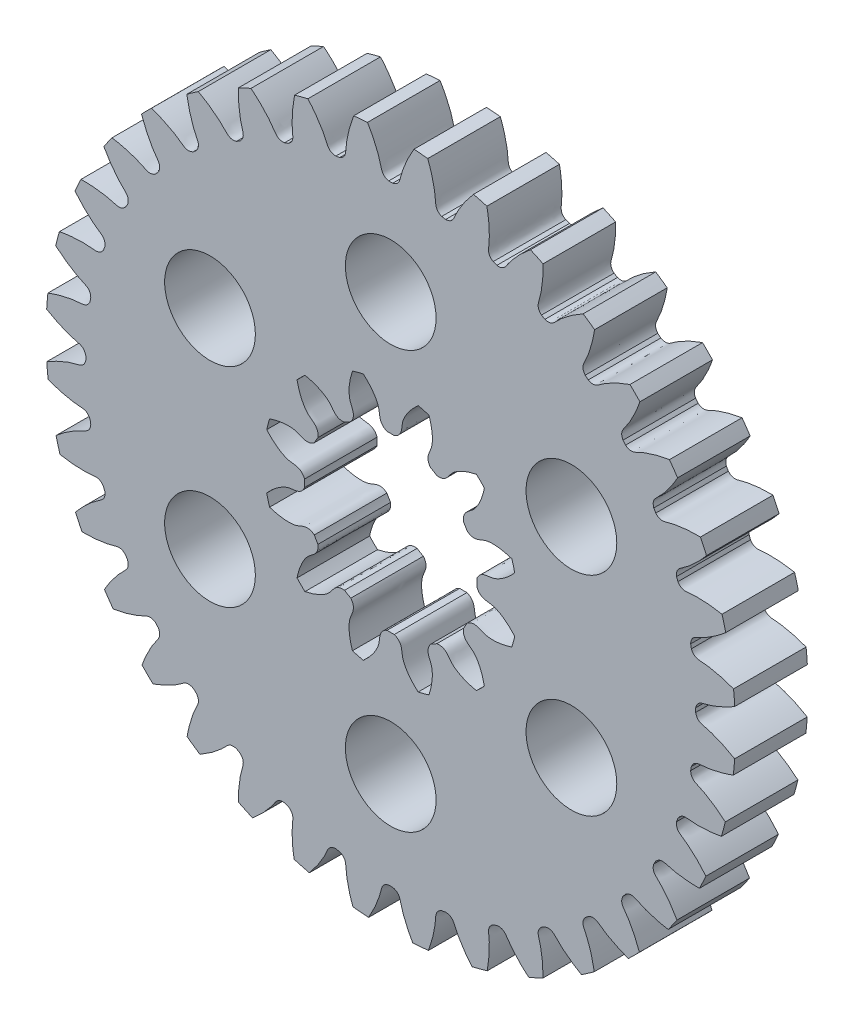
SolidWorks part; units mm, degrees
ref_plane "前视基准面" through (0, 0, 0) normal (0, 0, 1) x (1, 0, 0)
ref_plane "上视基准面" through (0, 0, 0) normal (0, 1, 0) x (1, 0, 0)
ref_plane "右视基准面" through (0, 0, 0) normal (1, 0, 0) x (0, 0, -1)
sketch "草图1" plane through (0, 0, 0) normal (0, 0, 1) x (1, 0, 0)
  arc A0 (-261.7659, -219.3873) -> (-261.9823, -219.4255) centre (-258.9656, -235.9016) ccw
  arc A1 (-258.8462, -219.1511) -> (-259.0659, -219.1511) centre (-258.956, -235.9007) ccw
  arc A2 (-256.9161, -217.0106) -> (-257.675, -216.944) centre (-258.956, -235.9007) ccw
  arc A3 (-255.9297, -219.4255) -> (-256.1461, -219.3873) centre (-258.9464, -235.9016) ccw
  arc A4 (-253.1052, -220.2021) -> (-253.3117, -220.127) centre (-258.9372, -235.9041) ccw
  arc A5 (-250.4585, -221.4574) -> (-250.6488, -221.3476) centre (-258.9285, -235.9081) ccw
  arc A6 (-248.07, -223.1533) -> (-248.2383, -223.012) centre (-258.9206, -235.9136) ccw
  arc A7 (-246.0122, -225.2381) -> (-246.1534, -225.0698) centre (-258.9138, -235.9204) ccw
  arc A8 (-244.3477, -227.6486) -> (-244.4576, -227.4583) centre (-258.9083, -235.9283) ccw
  arc A9 (-243.1271, -230.3116) -> (-243.2023, -230.1051) centre (-258.9042, -235.937) ccw
  arc A10 (-242.3875, -233.146) -> (-242.4256, -232.9296) centre (-258.9017, -235.9463) ccw
  arc A11 (-242.1512, -236.0658) -> (-242.1512, -235.846) centre (-258.9009, -235.9559) ccw
  arc A12 (-242.4256, -238.9822) -> (-242.3875, -238.7658) centre (-258.9017, -235.9655) ccw
  arc A13 (-243.2023, -241.8067) -> (-243.1271, -241.6002) centre (-258.9042, -235.9747) ccw
  arc A14 (-244.4576, -244.4534) -> (-244.3477, -244.2631) centre (-258.9083, -235.9835) ccw
  arc A15 (-246.1534, -246.842) -> (-246.0122, -246.6736) centre (-258.9138, -235.9913) ccw
  arc A16 (-248.2383, -248.8997) -> (-248.07, -248.7585) centre (-258.9206, -235.9981) ccw
  arc A17 (-250.6488, -250.5642) -> (-250.4585, -250.4543) centre (-258.9285, -236.0036) ccw
  arc A18 (-253.3117, -251.7848) -> (-253.1052, -251.7096) centre (-258.9372, -236.0077) ccw
  arc A19 (-256.1461, -252.5245) -> (-255.9297, -252.4863) centre (-258.9464, -236.0102) ccw
  arc A20 (-259.0659, -252.7607) -> (-258.8462, -252.7607) centre (-258.956, -236.011) ccw
  arc A21 (-261.9823, -252.4863) -> (-261.7659, -252.5245) centre (-258.9656, -236.0102) ccw
  arc A22 (-264.8068, -251.7096) -> (-264.6004, -251.7848) centre (-258.9749, -236.0077) ccw
  arc A23 (-267.4536, -250.4543) -> (-267.2633, -250.5642) centre (-258.9836, -236.0036) ccw
  arc A24 (-269.8421, -248.7585) -> (-269.6738, -248.8997) centre (-258.9915, -235.9981) ccw
  arc A25 (-271.8999, -246.6736) -> (-271.7586, -246.842) centre (-258.9983, -235.9913) ccw
  arc A26 (-273.5643, -244.2631) -> (-273.4545, -244.4534) centre (-259.0038, -235.9835) ccw
  arc A27 (-274.7849, -241.6002) -> (-274.7098, -241.8067) centre (-259.0079, -235.9747) ccw
  arc A28 (-275.5246, -238.7658) -> (-275.4864, -238.9822) centre (-259.0103, -235.9655) ccw
  arc A29 (-275.7608, -235.846) -> (-275.7608, -236.0658) centre (-259.0112, -235.9559) ccw
  arc A30 (-275.4864, -232.9296) -> (-275.5246, -233.146) centre (-259.0103, -235.9463) ccw
  arc A31 (-274.7098, -230.1051) -> (-274.7849, -230.3116) centre (-259.0079, -235.937) ccw
  arc A32 (-273.4545, -227.4583) -> (-273.5643, -227.6486) centre (-259.0038, -235.9283) ccw
  arc A33 (-271.7586, -225.0698) -> (-271.8999, -225.2381) centre (-258.9983, -235.9204) ccw
  arc A34 (-269.6738, -223.012) -> (-269.8421, -223.1533) centre (-258.9915, -235.9136) ccw
  arc A35 (-267.2633, -221.3476) -> (-267.4536, -221.4574) centre (-258.9836, -235.9081) ccw
  arc A36 (-264.6004, -220.127) -> (-264.8068, -220.2021) centre (-258.9749, -235.9041) ccw
  arc A37 (-253.6569, -217.6547) -> (-254.3942, -217.4565) centre (-258.956, -235.9007) ccw
  arc A38 (-250.5593, -218.8568) -> (-251.2538, -218.5319) centre (-258.956, -235.9007) ccw
  arc A39 (-247.7186, -220.5802) -> (-248.3498, -220.1366) centre (-258.956, -235.9007) ccw
  arc A40 (-245.2217, -222.7719) -> (-245.7703, -222.2209) centre (-258.956, -235.9007) ccw
  arc A41 (-243.145, -225.3645) -> (-243.5936, -224.7206) centre (-258.956, -235.9007) ccw
  arc A42 (-241.5521, -228.2783) -> (-241.8852, -227.5588) centre (-258.956, -235.9007) ccw
  arc A43 (-240.491, -231.4237) -> (-240.6963, -230.6488) centre (-258.956, -235.9007) ccw
  arc A44 (-239.9937, -234.7044) -> (-240.062, -233.8965) centre (-258.956, -235.9007) ccw
  arc A45 (-240.0746, -238.02) -> (-240.0007, -237.2032) centre (-258.956, -235.9007) ccw
  arc A46 (-240.7303, -241.2693) -> (-240.5134, -240.4689) centre (-258.956, -235.9007) ccw
  arc A47 (-241.9398, -244.3535) -> (-241.5837, -243.595) centre (-258.956, -235.9007) ccw
  arc A48 (-243.6656, -247.1792) -> (-243.1788, -246.4875) centre (-258.956, -235.9007) ccw
  arc A49 (-245.8545, -249.6611) -> (-245.2501, -249.0593) centre (-258.956, -235.9007) ccw
  arc A50 (-248.4392, -251.7247) -> (-247.7349, -251.2333) centre (-258.956, -235.9007) ccw
  arc A51 (-251.3412, -253.308) -> (-250.5583, -252.9441) centre (-258.956, -235.9007) ccw
  arc A52 (-254.4722, -254.3641) -> (-253.6351, -254.1405) centre (-258.956, -235.9007) ccw
  arc A53 (-257.7377, -254.8616) -> (-256.873, -254.7862) centre (-258.956, -235.9007) ccw
  arc A54 (-261.0391, -254.7862) -> (-260.1743, -254.8616) centre (-258.956, -235.9007) ccw
  arc A55 (-264.2769, -254.1405) -> (-263.4398, -254.3641) centre (-258.956, -235.9007) ccw
  arc A56 (-267.3538, -252.9441) -> (-266.5709, -253.308) centre (-258.956, -235.9007) ccw
  arc A57 (-270.1771, -251.2333) -> (-269.4728, -251.7247) centre (-258.956, -235.9007) ccw
  arc A58 (-272.6619, -249.0593) -> (-272.0576, -249.6611) centre (-258.956, -235.9007) ccw
  arc A59 (-274.7332, -246.4875) -> (-274.2464, -247.1792) centre (-258.956, -235.9007) ccw
  arc A60 (-276.3283, -243.595) -> (-275.9722, -244.3535) centre (-258.956, -235.9007) ccw
  arc A61 (-277.3987, -240.4689) -> (-277.1818, -241.2693) centre (-258.956, -235.9007) ccw
  arc A62 (-277.9113, -237.2032) -> (-277.8375, -238.02) centre (-258.956, -235.9007) ccw
  arc A63 (-277.85, -233.8965) -> (-277.9183, -234.7044) centre (-258.956, -235.9007) ccw
  arc A64 (-277.2157, -230.6488) -> (-277.421, -231.4237) centre (-258.956, -235.9007) ccw
  arc A65 (-276.0268, -227.5588) -> (-276.36, -228.2783) centre (-258.956, -235.9007) ccw
  arc A66 (-274.3184, -224.7206) -> (-274.767, -225.3645) centre (-258.956, -235.9007) ccw
  arc A67 (-272.1417, -222.2209) -> (-272.6904, -222.7719) centre (-258.956, -235.9007) ccw
  arc A68 (-269.5623, -220.1366) -> (-270.1935, -220.5802) centre (-258.956, -235.9007) ccw
  arc A69 (-266.6582, -218.5319) -> (-267.3527, -218.8568) centre (-258.956, -235.9007) ccw
  arc A70 (-263.5178, -217.4565) -> (-264.2552, -217.6547) centre (-258.956, -235.9007) ccw
  arc A71 (-260.237, -216.944) -> (-260.996, -217.0106) centre (-258.956, -235.9007) ccw
  arc A72 (-260.4688, -229.0661) -> (-261.0633, -229.2254) centre (-258.956, -235.9007) ccw
  arc A73 (-258.7552, -231.155) -> (-259.1569, -231.155) centre (-258.956, -235.9007) ccw
  arc A74 (-256.8488, -229.2254) -> (-257.4433, -229.0661) centre (-258.956, -235.9007) ccw
  arc A75 (-256.4092, -231.8912) -> (-256.7571, -231.6904) centre (-258.956, -235.9007) ccw
  arc A76 (-253.7935, -231.1734) -> (-254.2287, -230.7382) centre (-258.956, -235.9007) ccw
  arc A77 (-254.7457, -233.7018) -> (-254.9465, -233.3539) centre (-258.956, -235.9007) ccw
  arc A78 (-252.1214, -234.388) -> (-252.2807, -233.7935) centre (-258.956, -235.9007) ccw
  arc A79 (-254.2103, -236.1016) -> (-254.2103, -235.6999) centre (-258.956, -235.9007) ccw
  arc A80 (-252.2807, -238.008) -> (-252.1214, -237.4135) centre (-258.956, -235.9007) ccw
  arc A81 (-254.9465, -238.4475) -> (-254.7457, -238.0997) centre (-258.956, -235.9007) ccw
  arc A82 (-254.2287, -241.0633) -> (-253.7935, -240.6281) centre (-258.956, -235.9007) ccw
  arc A83 (-256.7571, -240.1111) -> (-256.4092, -239.9103) centre (-258.956, -235.9007) ccw
  arc A84 (-257.4433, -242.7353) -> (-256.8488, -242.576) centre (-258.956, -235.9007) ccw
  arc A85 (-259.1569, -240.6465) -> (-258.7552, -240.6465) centre (-258.956, -235.9007) ccw
  arc A86 (-261.0633, -242.576) -> (-260.4688, -242.7353) centre (-258.956, -235.9007) ccw
  arc A87 (-261.5028, -239.9103) -> (-261.155, -240.1111) centre (-258.956, -235.9007) ccw
  arc A88 (-264.1186, -240.6281) -> (-263.6834, -241.0633) centre (-258.956, -235.9007) ccw
  arc A89 (-263.1664, -238.0997) -> (-262.9655, -238.4475) centre (-258.956, -235.9007) ccw
  arc A90 (-265.7906, -237.4135) -> (-265.6313, -238.008) centre (-258.956, -235.9007) ccw
  arc A91 (-263.7018, -235.6999) -> (-263.7018, -236.1016) centre (-258.956, -235.9007) ccw
  arc A92 (-265.6313, -233.7935) -> (-265.7906, -234.388) centre (-258.956, -235.9007) ccw
  arc A93 (-262.9655, -233.3539) -> (-263.1664, -233.7018) centre (-258.956, -235.9007) ccw
  arc A94 (-263.6834, -230.7382) -> (-264.1186, -231.1734) centre (-258.956, -235.9007) ccw
  arc A95 (-261.155, -231.6904) -> (-261.5028, -231.8912) centre (-258.956, -235.9007) ccw
  circle A96 centre (-258.956, -224.4007) radius 2.5
  circle A97 centre (-268.9153, -230.1507) radius 2.5
  circle A98 centre (-268.9153, -241.6507) radius 2.5
  circle A99 centre (-258.956, -247.4007) radius 2.5
  circle A100 centre (-248.9967, -241.6507) radius 2.5
  circle A101 centre (-248.9967, -230.1507) radius 2.5
  spline S0 degree 3 poles (-261.7659, -219.3873) (-261.4254, -219.2453) (-261.4414, -218.9757) (-261.4164, -218.6828) (-261.4078, -218.5991) (-261.3923, -218.4743) (-261.3655, -218.3022) (-261.3213, -218.0772) (-261.2618, -217.8279) (-261.1851, -217.5551) (-261.0957, -217.2795) (-261.0288, -217.0962) (-260.996, -217.0106) knots 0 0 0 0 0.120371 0.133303 0.147364 0.162556 0.19633 0.234626 0.277443 0.324782 0.376641 0.422597 0.422597 0.422597 0.422597
  spline S1 degree 3 poles (-259.0659, -219.1511) (-259.426, -219.0703) (-259.457, -218.8021) (-259.5325, -218.518) (-259.5555, -218.437) (-259.5925, -218.3168) (-259.6487, -218.152) (-259.7313, -217.9381) (-259.8332, -217.7029) (-259.9561, -217.4475) (-260.092, -217.1917) (-260.1898, -217.0227) (-260.237, -216.944) knots 0 0 0 0 0.120371 0.133303 0.147364 0.162556 0.19633 0.234626 0.277443 0.324782 0.376641 0.422634 0.422634 0.422634 0.422634
  spline S2 degree 3 poles (-258.8462, -219.1511) (-258.4861, -219.0703) (-258.455, -218.8021) (-258.3796, -218.518) (-258.3565, -218.437) (-258.3196, -218.3168) (-258.2634, -218.152) (-258.1807, -217.9381) (-258.0789, -217.7029) (-257.956, -217.4475) (-257.82, -217.1917) (-257.7223, -217.0227) (-257.675, -216.944) knots 0 0 0 0 0.120371 0.133303 0.147364 0.162556 0.19633 0.234626 0.277443 0.324782 0.376641 0.422634 0.422634 0.422634 0.422634
  spline S3 degree 3 poles (-256.1461, -219.3873) (-256.4867, -219.2453) (-256.4707, -218.9757) (-256.4956, -218.6828) (-256.5043, -218.5991) (-256.5198, -218.4743) (-256.5466, -218.3022) (-256.5908, -218.0772) (-256.6503, -217.8279) (-256.7269, -217.5551) (-256.8164, -217.2795) (-256.8833, -217.0962) (-256.9161, -217.0106) knots 0 0 0 0 0.120371 0.133303 0.147364 0.162556 0.19633 0.234626 0.277443 0.324782 0.376641 0.422597 0.422597 0.422597 0.422597
  spline S4 degree 3 poles (-255.9297, -219.4255) (-255.5611, -219.4085) (-255.4839, -219.1497) (-255.3603, -218.883) (-255.3235, -218.8073) (-255.2663, -218.6953) (-255.1823, -218.5428) (-255.0638, -218.3465) (-254.9226, -218.1325) (-254.7572, -217.9024) (-254.5793, -217.6744) (-254.454, -217.5254) (-254.3942, -217.4565) knots 0 0 0 0 0.120371 0.133303 0.147364 0.162556 0.19633 0.234626 0.277443 0.324782 0.376641 0.422355 0.422355 0.422355 0.422355
  spline S5 degree 3 poles (-253.3117, -220.127) (-253.6224, -219.9279) (-253.5599, -219.6653) (-253.5336, -219.3725) (-253.5276, -219.2885) (-253.5212, -219.1629) (-253.5176, -218.9888) (-253.5221, -218.7596) (-253.5374, -218.5037) (-253.5655, -218.2217) (-253.6057, -217.9355) (-253.6396, -217.744) (-253.6569, -217.6547) knots 0 0 0 0 0.120371 0.133303 0.147364 0.162556 0.19633 0.234626 0.277443 0.324782 0.376641 0.422247 0.422247 0.422247 0.422247
  spline S6 degree 3 poles (-253.1052, -220.2021) (-252.7392, -220.2494) (-252.6183, -220.008) (-252.4502, -219.7668) (-252.4009, -219.6986) (-252.3251, -219.5983) (-252.2159, -219.4626) (-252.0651, -219.2899) (-251.8889, -219.1037) (-251.6861, -218.9058) (-251.4721, -218.713) (-251.3237, -218.5887) (-251.2538, -218.5319) knots 0 0 0 0 0.120371 0.133303 0.147364 0.162556 0.19633 0.234626 0.277443 0.324782 0.376641 0.421771 0.421771 0.421771 0.421771
  spline S7 degree 3 poles (-250.6488, -221.3476) (-250.9202, -221.0976) (-250.813, -220.8498) (-250.7363, -220.566) (-250.7158, -220.4844) (-250.6877, -220.3618) (-250.654, -220.1909) (-250.6186, -219.9644) (-250.5892, -219.7098) (-250.5679, -219.4272) (-250.5578, -219.1397) (-250.5579, -218.9465) (-250.5593, -218.8568) knots 0 0 0 0 0.120371 0.133303 0.147364 0.162556 0.19633 0.234626 0.277443 0.324782 0.376641 0.421594 0.421594 0.421594 0.421594
  spline S8 degree 3 poles (-250.4585, -221.4574) (-250.1063, -221.5675) (-249.9453, -221.3508) (-249.7379, -221.1424) (-249.6774, -221.0839) (-249.5853, -220.9982) (-249.4542, -220.8836) (-249.2757, -220.7397) (-249.0699, -220.5869) (-248.8358, -220.4272) (-248.5931, -220.2754) (-248.4269, -220.1796) (-248.3498, -220.1366) knots 0 0 0 0 0.120371 0.133303 0.147364 0.162556 0.19633 0.234626 0.277443 0.324782 0.376641 0.420899 0.420899 0.420899 0.420899
  spline S9 degree 3 poles (-248.2383, -223.012) (-248.4622, -222.7187) (-248.3136, -222.4933) (-248.1887, -222.2272) (-248.1544, -222.1503) (-248.1054, -222.0345) (-248.0425, -221.8721) (-247.9684, -221.6551) (-247.8952, -221.4095) (-247.8252, -221.1349) (-247.7657, -220.8553) (-247.7325, -220.6669) (-247.7186, -220.5802) knots 0 0 0 0 0.120371 0.133303 0.147364 0.162556 0.19633 0.234626 0.277443 0.324782 0.376641 0.420658 0.420658 0.420658 0.420658
  spline S10 degree 3 poles (-248.07, -223.1533) (-247.7422, -223.3229) (-247.546, -223.1374) (-247.3056, -222.9682) (-247.2359, -222.921) (-247.1303, -222.8527) (-246.9813, -222.7626) (-246.7805, -222.6518) (-246.5513, -222.5371) (-246.293, -222.4205) (-246.0297, -222.314) (-245.8516, -222.2492) (-245.7703, -222.2209) knots 0 0 0 0 0.120371 0.133303 0.147364 0.162556 0.19633 0.234626 0.277443 0.324782 0.376641 0.419767 0.419767 0.419767 0.419767
  spline S11 degree 3 poles (-246.1534, -225.0698) (-246.323, -224.7421) (-246.1375, -224.5459) (-245.9683, -224.3054) (-245.9212, -224.2357) (-245.8528, -224.1302) (-245.7627, -223.9812) (-245.652, -223.7804) (-245.5373, -223.5512) (-245.4206, -223.2929) (-245.3144, -223.0301) (-245.2497, -222.8526) (-245.2217, -222.7719) knots 0 0 0 0 0.120371 0.133303 0.147364 0.162556 0.19633 0.234626 0.277443 0.324782 0.376641 0.419468 0.419468 0.419468 0.419468
  spline S12 degree 3 poles (-246.0122, -225.2381) (-245.7189, -225.4621) (-245.4934, -225.3134) (-245.2273, -225.1886) (-245.1505, -225.1542) (-245.0346, -225.1052) (-244.8722, -225.0424) (-244.6553, -224.9682) (-244.4096, -224.895) (-244.135, -224.825) (-243.8598, -224.7664) (-243.6759, -224.7339) (-243.5936, -224.7206) knots 0 0 0 0 0.120371 0.133303 0.147364 0.162556 0.19633 0.234626 0.277443 0.324782 0.376641 0.418409 0.418409 0.418409 0.418409
  spline S13 degree 3 poles (-244.4576, -227.4583) (-244.5677, -227.1061) (-244.3509, -226.9451) (-244.1426, -226.7377) (-244.084, -226.6773) (-243.9984, -226.5852) (-243.8837, -226.4541) (-243.7399, -226.2756) (-243.5871, -226.0698) (-243.4273, -225.8357) (-243.2786, -225.5977) (-243.1854, -225.4366) (-243.145, -225.3645) knots 0 0 0 0 0.120371 0.133303 0.147364 0.162556 0.19633 0.234626 0.277443 0.324782 0.376641 0.418059 0.418059 0.418059 0.418059
  spline S14 degree 3 poles (-244.3477, -227.6486) (-244.0977, -227.9201) (-243.8499, -227.8129) (-243.5661, -227.7361) (-243.4845, -227.7156) (-243.3619, -227.6875) (-243.1911, -227.6538) (-242.9646, -227.6184) (-242.7099, -227.589) (-242.4273, -227.5678) (-242.1492, -227.558) (-241.9655, -227.5578) (-241.8852, -227.5588) knots 0 0 0 0 0.120371 0.133303 0.147364 0.162556 0.19633 0.234626 0.277443 0.324782 0.376641 0.416867 0.416867 0.416867 0.416867
  spline S15 degree 3 poles (-243.2023, -230.1051) (-243.2495, -229.7391) (-243.0081, -229.6182) (-242.7669, -229.4501) (-242.6987, -229.4007) (-242.5984, -229.3249) (-242.4628, -229.2157) (-242.2901, -229.0649) (-242.1038, -228.8888) (-241.9059, -228.6859) (-241.7202, -228.4798) (-241.6024, -228.3398) (-241.5521, -228.2783) knots 0 0 0 0 0.120371 0.133303 0.147364 0.162556 0.19633 0.234626 0.277443 0.324782 0.376641 0.416476 0.416476 0.416476 0.416476
  spline S16 degree 3 poles (-243.1271, -230.3116) (-242.9281, -230.6223) (-242.6654, -230.5597) (-242.3726, -230.5334) (-242.2886, -230.5274) (-242.1631, -230.521) (-241.9889, -230.5175) (-241.7597, -230.522) (-241.5038, -230.5372) (-241.2218, -230.5654) (-240.9496, -230.6036) (-240.7719, -230.6346) (-240.6963, -230.6488) knots 0 0 0 0 0.120371 0.133303 0.147364 0.162556 0.19633 0.234626 0.277443 0.324782 0.376641 0.415189 0.415189 0.415189 0.415189
  spline S17 degree 3 poles (-242.4256, -232.9296) (-242.4086, -232.5609) (-242.1498, -232.4838) (-241.8831, -232.3601) (-241.8074, -232.3234) (-241.6955, -232.2661) (-241.5429, -232.1821) (-241.3466, -232.0636) (-241.1327, -231.9225) (-240.9025, -231.7571) (-240.6865, -231.5884) (-240.5487, -231.4733) (-240.491, -231.4237) knots 0 0 0 0 0.120371 0.133303 0.147364 0.162556 0.19633 0.234626 0.277443 0.324782 0.376641 0.414768 0.414768 0.414768 0.414768
  spline S18 degree 3 poles (-242.3875, -233.146) (-242.2454, -233.4866) (-241.9759, -233.4705) (-241.683, -233.4955) (-241.5992, -233.5042) (-241.4744, -233.5196) (-241.3023, -233.5464) (-241.0774, -233.5907) (-240.828, -233.6501) (-240.5552, -233.7268) (-240.2971, -233.8106) (-240.1307, -233.8707) (-240.062, -233.8965) knots 0 0 0 0 0.120371 0.133303 0.147364 0.162556 0.19633 0.234626 0.277443 0.324782 0.376641 0.413425 0.413425 0.413425 0.413425
  spline S19 degree 3 poles (-242.1512, -235.846) (-242.0705, -235.4859) (-241.8022, -235.4549) (-241.5181, -235.3794) (-241.4372, -235.3564) (-241.317, -235.3195) (-241.1521, -235.2632) (-240.9383, -235.1806) (-240.7031, -235.0787) (-240.4477, -234.9559) (-240.2088, -234.8289) (-240.0562, -234.7413) (-239.9937, -234.7044) knots 0 0 0 0 0.120371 0.133303 0.147364 0.162556 0.19633 0.234626 0.277443 0.324782 0.376641 0.412986 0.412986 0.412986 0.412986
  spline S20 degree 3 poles (-242.1512, -236.0658) (-242.0705, -236.4258) (-241.8022, -236.4569) (-241.5181, -236.5323) (-241.4372, -236.5554) (-241.317, -236.5923) (-241.1521, -236.6485) (-240.9383, -236.7312) (-240.7031, -236.833) (-240.4477, -236.9559) (-240.2112, -237.0816) (-240.0609, -237.1677) (-240.0007, -237.2032) knots 0 0 0 0 0.120371 0.133303 0.147364 0.162556 0.19633 0.234626 0.277443 0.324782 0.376641 0.411628 0.411628 0.411628 0.411628
  spline S21 degree 3 poles (-242.3875, -238.7658) (-242.2454, -238.4252) (-241.9759, -238.4412) (-241.683, -238.4163) (-241.5992, -238.4076) (-241.4744, -238.3921) (-241.3023, -238.3654) (-241.0774, -238.3211) (-240.828, -238.2617) (-240.5552, -238.185) (-240.3013, -238.1026) (-240.1391, -238.0442) (-240.0746, -238.02) knots 0 0 0 0 0.120371 0.133303 0.147364 0.162556 0.19633 0.234626 0.277443 0.324782 0.376641 0.411185 0.411185 0.411185 0.411185
  spline S22 degree 3 poles (-242.4256, -238.9822) (-242.4086, -239.3508) (-242.1498, -239.428) (-241.8831, -239.5516) (-241.8074, -239.5884) (-241.6955, -239.6456) (-241.5429, -239.7296) (-241.3466, -239.8482) (-241.1327, -239.9893) (-240.9025, -240.1547) (-240.6942, -240.3173) (-240.5638, -240.4259) (-240.5134, -240.4689) knots 0 0 0 0 0.120371 0.133303 0.147364 0.162556 0.19633 0.234626 0.277443 0.324782 0.376641 0.409854 0.409854 0.409854 0.409854
  spline S23 degree 3 poles (-243.1271, -241.6002) (-242.9281, -241.2895) (-242.6654, -241.352) (-242.3726, -241.3783) (-242.2886, -241.3843) (-242.1631, -241.3908) (-241.9889, -241.3943) (-241.7597, -241.3898) (-241.5038, -241.3745) (-241.2218, -241.3464) (-240.961, -241.3098) (-240.7946, -241.2811) (-240.7303, -241.2693) knots 0 0 0 0 0.120371 0.133303 0.147364 0.162556 0.19633 0.234626 0.277443 0.324782 0.376641 0.40942 0.40942 0.40942 0.40942
  spline S24 degree 3 poles (-243.2023, -241.8067) (-243.2495, -242.1727) (-243.0081, -242.2936) (-242.7669, -242.4617) (-242.6987, -242.511) (-242.5984, -242.5868) (-242.4628, -242.6961) (-242.2901, -242.8469) (-242.1038, -243.023) (-241.9059, -243.2258) (-241.7313, -243.4196) (-241.6238, -243.5466) (-241.5837, -243.595) knots 0 0 0 0 0.120371 0.133303 0.147364 0.162556 0.19633 0.234626 0.277443 0.324782 0.376641 0.408156 0.408156 0.408156 0.408156
  spline S25 degree 3 poles (-244.3477, -244.2631) (-244.0977, -243.9917) (-243.8499, -244.0989) (-243.5661, -244.1756) (-243.4845, -244.1961) (-243.3619, -244.2243) (-243.1911, -244.258) (-242.9646, -244.2933) (-242.7099, -244.3227) (-242.4273, -244.344) (-242.1674, -244.3532) (-242.0019, -244.3539) (-241.9398, -244.3535) knots 0 0 0 0 0.120371 0.133303 0.147364 0.162556 0.19633 0.234626 0.277443 0.324782 0.376641 0.407744 0.407744 0.407744 0.407744
  spline S26 degree 3 poles (-244.4576, -244.4534) (-244.5677, -244.8057) (-244.3509, -244.9666) (-244.1426, -245.174) (-244.084, -245.2345) (-243.9984, -245.3266) (-243.8837, -245.4577) (-243.7399, -245.6362) (-243.5871, -245.842) (-243.4273, -246.0761) (-243.2907, -246.2946) (-243.2084, -246.4356) (-243.1788, -246.4875) knots 0 0 0 0 0.120371 0.133303 0.147364 0.162556 0.19633 0.234626 0.277443 0.324782 0.376641 0.406585 0.406585 0.406585 0.406585
  spline S27 degree 3 poles (-246.0122, -246.6736) (-245.7189, -246.4497) (-245.4934, -246.5983) (-245.2273, -246.7232) (-245.1505, -246.7575) (-245.0346, -246.8065) (-244.8722, -246.8694) (-244.6553, -246.9436) (-244.4096, -247.0167) (-244.135, -247.0868) (-243.8837, -247.1403) (-243.7238, -247.1693) (-243.6656, -247.1792) knots 0 0 0 0 0.120371 0.133303 0.147364 0.162556 0.19633 0.234626 0.277443 0.324782 0.376641 0.406209 0.406209 0.406209 0.406209
  spline S28 degree 3 poles (-246.1534, -246.842) (-246.323, -247.1697) (-246.1375, -247.3659) (-245.9683, -247.6063) (-245.9212, -247.676) (-245.8528, -247.7816) (-245.7627, -247.9306) (-245.652, -248.1314) (-245.5373, -248.3606) (-245.4206, -248.6189) (-245.325, -248.8552) (-245.2693, -249.0057) (-245.2501, -249.0593) knots 0 0 0 0 0.120371 0.133303 0.147364 0.162556 0.19633 0.234626 0.277443 0.324782 0.376641 0.405188 0.405188 0.405188 0.405188
  spline S29 degree 3 poles (-248.07, -248.7585) (-247.7422, -248.5889) (-247.546, -248.7744) (-247.3056, -248.9436) (-247.2359, -248.9908) (-247.1303, -249.0591) (-246.9813, -249.1492) (-246.7805, -249.2599) (-246.5513, -249.3747) (-246.293, -249.4913) (-246.0573, -249.5866) (-245.9074, -249.6421) (-245.8545, -249.6611) knots 0 0 0 0 0.120371 0.133303 0.147364 0.162556 0.19633 0.234626 0.277443 0.324782 0.376641 0.404861 0.404861 0.404861 0.404861
  spline S30 degree 3 poles (-248.2383, -248.8997) (-248.4622, -249.1931) (-248.3136, -249.4185) (-248.1887, -249.6846) (-248.1544, -249.7615) (-248.1054, -249.8773) (-248.0425, -250.0397) (-247.9684, -250.2566) (-247.8952, -250.5023) (-247.8252, -250.7769) (-247.7726, -251.024) (-247.7442, -251.1795) (-247.7349, -251.2333) knots 0 0 0 0 0.120371 0.133303 0.147364 0.162556 0.19633 0.234626 0.277443 0.324782 0.376641 0.404007 0.404007 0.404007 0.404007
  spline S31 degree 3 poles (-250.4585, -250.4543) (-250.1063, -250.3442) (-249.9453, -250.561) (-249.7379, -250.7693) (-249.6774, -250.8279) (-249.5853, -250.9136) (-249.4542, -251.0282) (-249.2757, -251.1721) (-249.0699, -251.3249) (-248.8358, -251.4846) (-248.6221, -251.6182) (-248.4861, -251.6978) (-248.4392, -251.7247) knots 0 0 0 0 0.120371 0.133303 0.147364 0.162556 0.19633 0.234626 0.277443 0.324782 0.376641 0.40374 0.40374 0.40374 0.40374
  spline S32 degree 3 poles (-250.6488, -250.5642) (-250.9202, -250.8142) (-250.813, -251.062) (-250.7363, -251.3458) (-250.7158, -251.4274) (-250.6877, -251.55) (-250.6539, -251.7208) (-250.6186, -251.9474) (-250.5892, -252.202) (-250.5679, -252.4846) (-250.5591, -252.7352) (-250.5581, -252.8914) (-250.5583, -252.9441) knots 0 0 0 0 0.120371 0.133303 0.147364 0.162556 0.19633 0.234626 0.277443 0.324782 0.376641 0.403078 0.403078 0.403078 0.403078
  spline S33 degree 3 poles (-253.1052, -251.7096) (-252.7392, -251.6624) (-252.6183, -251.9038) (-252.4502, -252.145) (-252.4009, -252.2132) (-252.3251, -252.3135) (-252.2159, -252.4492) (-252.0651, -252.6219) (-251.8889, -252.8081) (-251.6861, -253.006) (-251.5001, -253.1736) (-251.3814, -253.2745) (-251.3412, -253.308) knots 0 0 0 0 0.120371 0.133303 0.147364 0.162556 0.19633 0.234626 0.277443 0.324782 0.376641 0.40288 0.40288 0.40288 0.40288
  spline S34 degree 3 poles (-253.3117, -251.7848) (-253.6224, -251.9839) (-253.5599, -252.2465) (-253.5336, -252.5393) (-253.5276, -252.6233) (-253.5212, -252.7489) (-253.5176, -252.923) (-253.5221, -253.1522) (-253.5374, -253.4081) (-253.5655, -253.6901) (-253.6002, -253.9371) (-253.6261, -254.0898) (-253.6351, -254.1405) knots 0 0 0 0 0.120371 0.133303 0.147364 0.162556 0.19633 0.234626 0.277443 0.324782 0.376641 0.402428 0.402428 0.402428 0.402428
  spline S35 degree 3 poles (-255.9297, -252.4863) (-255.5611, -252.5033) (-255.4839, -252.7621) (-255.3603, -253.0288) (-255.3235, -253.1045) (-255.2663, -253.2165) (-255.1823, -253.369) (-255.0638, -253.5653) (-254.9226, -253.7792) (-254.7572, -254.0094) (-254.6039, -254.2058) (-254.5052, -254.3249) (-254.4722, -254.3641) knots 0 0 0 0 0.120371 0.133303 0.147364 0.162556 0.19633 0.234626 0.277443 0.324782 0.376641 0.402306 0.402306 0.402306 0.402306
  spline S36 degree 3 poles (-256.1461, -252.5245) (-256.4867, -252.6665) (-256.4707, -252.9361) (-256.4956, -253.229) (-256.5043, -253.3127) (-256.5198, -253.4375) (-256.5466, -253.6096) (-256.5908, -253.8345) (-256.6502, -254.0839) (-256.7269, -254.3567) (-256.8037, -254.5933) (-256.8555, -254.7386) (-256.873, -254.7862) knots 0 0 0 0 0.120371 0.133303 0.147364 0.162556 0.19633 0.234626 0.277443 0.324782 0.376641 0.402077 0.402077 0.402077 0.402077
  spline S37 degree 3 poles (-258.8462, -252.7607) (-258.4861, -252.8414) (-258.455, -253.1097) (-258.3796, -253.3938) (-258.3565, -253.4747) (-258.3196, -253.595) (-258.2634, -253.7598) (-258.1807, -253.9736) (-258.0789, -254.2089) (-257.956, -254.4642) (-257.8393, -254.6838) (-257.7631, -254.8178) (-257.7377, -254.8616) knots 0 0 0 0 0.120371 0.133303 0.147364 0.162556 0.19633 0.234626 0.277443 0.324782 0.376641 0.402036 0.402036 0.402036 0.402036
  spline S38 degree 3 poles (-259.0659, -252.7607) (-259.426, -252.8414) (-259.457, -253.1097) (-259.5325, -253.3938) (-259.5555, -253.4747) (-259.5925, -253.595) (-259.6487, -253.7598) (-259.7313, -253.9736) (-259.8332, -254.2089) (-259.9561, -254.4642) (-260.0727, -254.6838) (-260.1489, -254.8178) (-260.1743, -254.8616) knots 0 0 0 0 0.120371 0.133303 0.147364 0.162556 0.19633 0.234626 0.277443 0.324782 0.376641 0.402036 0.402036 0.402036 0.402036
  spline S39 degree 3 poles (-261.7659, -252.5245) (-261.4254, -252.6665) (-261.4414, -252.9361) (-261.4164, -253.229) (-261.4078, -253.3127) (-261.3923, -253.4375) (-261.3655, -253.6096) (-261.3213, -253.8345) (-261.2618, -254.0839) (-261.1851, -254.3567) (-261.1083, -254.5933) (-261.0566, -254.7386) (-261.0391, -254.7862) knots 0 0 0 0 0.120371 0.133303 0.147364 0.162556 0.19633 0.234626 0.277443 0.324782 0.376641 0.402077 0.402077 0.402077 0.402077
  spline S40 degree 3 poles (-261.9823, -252.4863) (-262.351, -252.5033) (-262.4281, -252.7621) (-262.5518, -253.0288) (-262.5885, -253.1045) (-262.6458, -253.2165) (-262.7298, -253.369) (-262.8483, -253.5653) (-262.9894, -253.7792) (-263.1548, -254.0094) (-263.3082, -254.2058) (-263.4068, -254.3249) (-263.4398, -254.3641) knots 0 0 0 0 0.120371 0.133303 0.147364 0.162556 0.19633 0.234626 0.277443 0.324782 0.376641 0.402307 0.402307 0.402307 0.402307
  spline S41 degree 3 poles (-264.6004, -251.7848) (-264.2896, -251.9839) (-264.3522, -252.2465) (-264.3785, -252.5393) (-264.3845, -252.6233) (-264.3909, -252.7489) (-264.3944, -252.923) (-264.3899, -253.1522) (-264.3747, -253.4081) (-264.3465, -253.6901) (-264.3119, -253.9371) (-264.286, -254.0898) (-264.2769, -254.1405) knots 0 0 0 0 0.120371 0.133303 0.147364 0.162556 0.19633 0.234626 0.277443 0.324782 0.376641 0.402428 0.402428 0.402428 0.402428
  spline S42 degree 3 poles (-264.8068, -251.7096) (-265.1728, -251.6624) (-265.2937, -251.9038) (-265.4618, -252.145) (-265.5112, -252.2132) (-265.587, -252.3135) (-265.6962, -252.4492) (-265.847, -252.6219) (-266.0232, -252.8081) (-266.226, -253.006) (-266.412, -253.1736) (-266.5307, -253.2745) (-266.5709, -253.308) knots 0 0 0 0 0.120371 0.133303 0.147364 0.162556 0.19633 0.234626 0.277443 0.324782 0.376641 0.40288 0.40288 0.40288 0.40288
  spline S43 degree 3 poles (-267.2633, -250.5642) (-266.9918, -250.8142) (-267.099, -251.062) (-267.1758, -251.3458) (-267.1963, -251.4274) (-267.2244, -251.55) (-267.2581, -251.7208) (-267.2935, -251.9474) (-267.3229, -252.202) (-267.3441, -252.4846) (-267.353, -252.7352) (-267.354, -252.8914) (-267.3538, -252.9441) knots 0 0 0 0 0.120371 0.133303 0.147364 0.162556 0.19633 0.234626 0.277443 0.324782 0.376641 0.403078 0.403078 0.403078 0.403078
  spline S44 degree 3 poles (-267.4536, -250.4543) (-267.8058, -250.3442) (-267.9668, -250.561) (-268.1742, -250.7693) (-268.2346, -250.8279) (-268.3267, -250.9136) (-268.4578, -251.0282) (-268.6363, -251.1721) (-268.8421, -251.3249) (-269.0763, -251.4846) (-269.29, -251.6182) (-269.4259, -251.6978) (-269.4728, -251.7247) knots 0 0 0 0 0.120371 0.133303 0.147364 0.162556 0.19633 0.234626 0.277443 0.324782 0.376641 0.40374 0.40374 0.40374 0.40374
  spline S45 degree 3 poles (-269.6738, -248.8997) (-269.4498, -249.1931) (-269.5985, -249.4185) (-269.7233, -249.6846) (-269.7577, -249.7615) (-269.8067, -249.8773) (-269.8695, -250.0397) (-269.9437, -250.2566) (-270.0169, -250.5023) (-270.0869, -250.7769) (-270.1395, -251.024) (-270.1679, -251.1795) (-270.1771, -251.2333) knots 0 0 0 0 0.120371 0.133303 0.147364 0.162556 0.19633 0.234626 0.277443 0.324782 0.376641 0.404007 0.404007 0.404007 0.404007
  spline S46 degree 3 poles (-269.8421, -248.7585) (-270.1699, -248.5889) (-270.366, -248.7744) (-270.6065, -248.9436) (-270.6762, -248.9908) (-270.7817, -249.0591) (-270.9307, -249.1492) (-271.1315, -249.2599) (-271.3607, -249.3747) (-271.619, -249.4913) (-271.8548, -249.5866) (-272.0046, -249.6421) (-272.0576, -249.6611) knots 0 0 0 0 0.120371 0.133303 0.147364 0.162556 0.19633 0.234626 0.277443 0.324782 0.376641 0.404861 0.404861 0.404861 0.404861
  spline S47 degree 3 poles (-271.7586, -246.842) (-271.589, -247.1697) (-271.7746, -247.3659) (-271.9437, -247.6063) (-271.9909, -247.676) (-272.0592, -247.7816) (-272.1494, -247.9306) (-272.2601, -248.1314) (-272.3748, -248.3606) (-272.4914, -248.6189) (-272.587, -248.8552) (-272.6427, -249.0057) (-272.6619, -249.0593) knots 0 0 0 0 0.120371 0.133303 0.147364 0.162556 0.19633 0.234626 0.277443 0.324782 0.376641 0.405188 0.405188 0.405188 0.405188
  spline S48 degree 3 poles (-271.8999, -246.6736) (-272.1932, -246.4497) (-272.4186, -246.5983) (-272.6848, -246.7232) (-272.7616, -246.7575) (-272.8774, -246.8065) (-273.0398, -246.8694) (-273.2568, -246.9436) (-273.5024, -247.0167) (-273.7771, -247.0868) (-274.0284, -247.1403) (-274.1883, -247.1693) (-274.2464, -247.1792) knots 0 0 0 0 0.120371 0.133303 0.147364 0.162556 0.19633 0.234626 0.277443 0.324782 0.376641 0.406209 0.406209 0.406209 0.406209
  spline S49 degree 3 poles (-273.4545, -244.4534) (-273.3444, -244.8057) (-273.5611, -244.9667) (-273.7695, -245.174) (-273.828, -245.2345) (-273.9137, -245.3266) (-274.0283, -245.4577) (-274.1722, -245.6362) (-274.325, -245.842) (-274.4847, -246.0761) (-274.6213, -246.2946) (-274.7037, -246.4356) (-274.7332, -246.4875) knots 0 0 0 0 0.120371 0.133303 0.147364 0.162556 0.19633 0.234626 0.277443 0.324782 0.376641 0.406585 0.406585 0.406585 0.406585
  spline S50 degree 3 poles (-273.5643, -244.2631) (-273.8143, -243.9917) (-274.0621, -244.0989) (-274.3459, -244.1756) (-274.4275, -244.1961) (-274.5501, -244.2243) (-274.721, -244.258) (-274.9475, -244.2933) (-275.2021, -244.3227) (-275.4847, -244.344) (-275.7446, -244.3532) (-275.9102, -244.3539) (-275.9722, -244.3535) knots 0 0 0 0 0.120371 0.133303 0.147364 0.162556 0.19633 0.234626 0.277443 0.324782 0.376641 0.407744 0.407744 0.407744 0.407744
  spline S51 degree 3 poles (-274.7098, -241.8067) (-274.6625, -242.1727) (-274.904, -242.2936) (-275.1451, -242.4617) (-275.2133, -242.511) (-275.3137, -242.5868) (-275.4493, -242.6961) (-275.622, -242.8469) (-275.8082, -243.023) (-276.0062, -243.2258) (-276.1808, -243.4196) (-276.2883, -243.5466) (-276.3283, -243.595) knots 0 0 0 0 0.120371 0.133303 0.147364 0.162556 0.19633 0.234626 0.277443 0.324782 0.376641 0.408156 0.408156 0.408156 0.408156
  spline S52 degree 3 poles (-274.7849, -241.6002) (-274.984, -241.2895) (-275.2467, -241.352) (-275.5394, -241.3783) (-275.6234, -241.3843) (-275.749, -241.3908) (-275.9231, -241.3943) (-276.1523, -241.3898) (-276.4082, -241.3745) (-276.6902, -241.3464) (-276.951, -241.3098) (-277.1175, -241.2811) (-277.1818, -241.2693) knots 0 0 0 0 0.120371 0.133303 0.147364 0.162556 0.19633 0.234626 0.277443 0.324782 0.376641 0.40942 0.40942 0.40942 0.40942
  spline S53 degree 3 poles (-275.4864, -238.9822) (-275.5034, -239.3509) (-275.7622, -239.428) (-276.0289, -239.5516) (-276.1046, -239.5884) (-276.2166, -239.6456) (-276.3691, -239.7296) (-276.5654, -239.8482) (-276.7794, -239.9893) (-277.0095, -240.1547) (-277.2178, -240.3173) (-277.3483, -240.4259) (-277.3987, -240.4689) knots 0 0 0 0 0.120371 0.133303 0.147364 0.162556 0.19633 0.234626 0.277443 0.324782 0.376641 0.409855 0.409855 0.409855 0.409855
  spline S54 degree 3 poles (-275.5246, -238.7658) (-275.6667, -238.4252) (-275.9362, -238.4412) (-276.2291, -238.4163) (-276.3128, -238.4076) (-276.4376, -238.3921) (-276.6097, -238.3654) (-276.8347, -238.3211) (-277.084, -238.2617) (-277.3569, -238.185) (-277.6107, -238.1026) (-277.7729, -238.0442) (-277.8375, -238.02) knots 0 0 0 0 0.120371 0.133303 0.147364 0.162556 0.19633 0.234626 0.277443 0.324782 0.376641 0.411185 0.411185 0.411185 0.411185
  spline S55 degree 3 poles (-275.7608, -236.0658) (-275.8416, -236.4258) (-276.1098, -236.4569) (-276.3939, -236.5323) (-276.4749, -236.5554) (-276.5951, -236.5923) (-276.7599, -236.6485) (-276.9738, -236.7312) (-277.209, -236.833) (-277.4644, -236.9559) (-277.7009, -237.0816) (-277.8512, -237.1677) (-277.9113, -237.2032) knots 0 0 0 0 0.120371 0.133303 0.147364 0.162556 0.19633 0.234626 0.277443 0.324782 0.376641 0.411629 0.411629 0.411629 0.411629
  spline S56 degree 3 poles (-275.7608, -235.846) (-275.8416, -235.4859) (-276.1098, -235.4549) (-276.3939, -235.3794) (-276.4749, -235.3564) (-276.5951, -235.3195) (-276.7599, -235.2632) (-276.9738, -235.1806) (-277.209, -235.0787) (-277.4644, -234.9559) (-277.7032, -234.8289) (-277.8559, -234.7413) (-277.9183, -234.7044) knots 0 0 0 0 0.120371 0.133303 0.147364 0.162556 0.19633 0.234626 0.277443 0.324782 0.376641 0.412986 0.412986 0.412986 0.412986
  spline S57 degree 3 poles (-275.5246, -233.146) (-275.6667, -233.4866) (-275.9362, -233.4705) (-276.2291, -233.4955) (-276.3128, -233.5042) (-276.4376, -233.5197) (-276.6097, -233.5464) (-276.8347, -233.5907) (-277.084, -233.6501) (-277.3569, -233.7268) (-277.615, -233.8106) (-277.7813, -233.8707) (-277.85, -233.8965) knots 0 0 0 0 0.120371 0.133303 0.147364 0.162556 0.19633 0.234626 0.277443 0.324782 0.376641 0.413425 0.413425 0.413425 0.413425
  spline S58 degree 3 poles (-275.4864, -232.9296) (-275.5034, -232.5609) (-275.7622, -232.4838) (-276.0289, -232.3601) (-276.1046, -232.3234) (-276.2166, -232.2661) (-276.3691, -232.1821) (-276.5654, -232.0636) (-276.7794, -231.9225) (-277.0095, -231.7571) (-277.2255, -231.5884) (-277.3633, -231.4733) (-277.421, -231.4237) knots 0 0 0 0 0.120371 0.133303 0.147364 0.162556 0.19633 0.234626 0.277443 0.324782 0.376641 0.414768 0.414768 0.414768 0.414768
  spline S59 degree 3 poles (-274.7849, -230.3116) (-274.984, -230.6223) (-275.2467, -230.5597) (-275.5394, -230.5334) (-275.6234, -230.5274) (-275.749, -230.521) (-275.9231, -230.5175) (-276.1523, -230.522) (-276.4082, -230.5372) (-276.6902, -230.5654) (-276.9624, -230.6036) (-277.1402, -230.6346) (-277.2157, -230.6488) knots 0 0 0 0 0.120371 0.133303 0.147364 0.162556 0.19633 0.234626 0.277443 0.324782 0.376641 0.415189 0.415189 0.415189 0.415189
  spline S60 degree 3 poles (-274.7098, -230.1051) (-274.6625, -229.7391) (-274.904, -229.6182) (-275.1451, -229.4501) (-275.2133, -229.4007) (-275.3137, -229.3249) (-275.4493, -229.2157) (-275.622, -229.0649) (-275.8082, -228.8888) (-276.0062, -228.6859) (-276.1919, -228.4798) (-276.3097, -228.3398) (-276.36, -228.2783) knots 0 0 0 0 0.120371 0.133303 0.147364 0.162556 0.19633 0.234626 0.277443 0.324782 0.376641 0.416477 0.416477 0.416477 0.416477
  spline S61 degree 3 poles (-273.5643, -227.6486) (-273.8143, -227.9201) (-274.0621, -227.8129) (-274.3459, -227.7361) (-274.4275, -227.7156) (-274.5501, -227.6875) (-274.721, -227.6538) (-274.9475, -227.6184) (-275.2021, -227.589) (-275.4847, -227.5678) (-275.7628, -227.558) (-275.9466, -227.5578) (-276.0268, -227.5588) knots 0 0 0 0 0.120371 0.133303 0.147364 0.162556 0.19633 0.234626 0.277443 0.324782 0.376641 0.416867 0.416867 0.416867 0.416867
  spline S62 degree 3 poles (-273.4545, -227.4583) (-273.3444, -227.1061) (-273.5611, -226.9451) (-273.7695, -226.7377) (-273.8281, -226.6773) (-273.9137, -226.5852) (-274.0283, -226.4541) (-274.1722, -226.2756) (-274.325, -226.0698) (-274.4847, -225.8357) (-274.6335, -225.5977) (-274.7267, -225.4366) (-274.767, -225.3645) knots 0 0 0 0 0.120371 0.133303 0.147364 0.162556 0.19633 0.234626 0.277443 0.324782 0.376641 0.418059 0.418059 0.418059 0.418059
  spline S63 degree 3 poles (-271.8999, -225.2381) (-272.1932, -225.4621) (-272.4186, -225.3134) (-272.6848, -225.1886) (-272.7616, -225.1542) (-272.8774, -225.1052) (-273.0398, -225.0424) (-273.2568, -224.9682) (-273.5024, -224.895) (-273.7771, -224.825) (-274.0522, -224.7664) (-274.2362, -224.7339) (-274.3184, -224.7206) knots 0 0 0 0 0.120371 0.133303 0.147364 0.162556 0.19633 0.234626 0.277443 0.324782 0.376641 0.418409 0.418409 0.418409 0.418409
  spline S64 degree 3 poles (-271.7586, -225.0698) (-271.589, -224.7421) (-271.7746, -224.5459) (-271.9437, -224.3054) (-271.9909, -224.2357) (-272.0592, -224.1302) (-272.1494, -223.9812) (-272.2601, -223.7804) (-272.3748, -223.5512) (-272.4914, -223.2929) (-272.5977, -223.0301) (-272.6624, -222.8526) (-272.6904, -222.7719) knots 0 0 0 0 0.120371 0.133303 0.147364 0.162556 0.19633 0.234626 0.277443 0.324782 0.376641 0.419468 0.419468 0.419468 0.419468
  spline S65 degree 3 poles (-269.8421, -223.1533) (-270.1699, -223.3229) (-270.366, -223.1374) (-270.6065, -222.9682) (-270.6762, -222.921) (-270.7817, -222.8527) (-270.9307, -222.7626) (-271.1315, -222.6518) (-271.3607, -222.5371) (-271.619, -222.4205) (-271.8823, -222.314) (-272.0604, -222.2492) (-272.1417, -222.2209) knots 0 0 0 0 0.120371 0.133303 0.147364 0.162556 0.19633 0.234626 0.277443 0.324782 0.376641 0.419767 0.419767 0.419767 0.419767
  spline S66 degree 3 poles (-269.6738, -223.012) (-269.4498, -222.7187) (-269.5985, -222.4933) (-269.7233, -222.2272) (-269.7577, -222.1503) (-269.8067, -222.0345) (-269.8695, -221.8721) (-269.9437, -221.6551) (-270.0169, -221.4095) (-270.0869, -221.1349) (-270.1464, -220.8553) (-270.1796, -220.6669) (-270.1935, -220.5802) knots 0 0 0 0 0.120371 0.133303 0.147364 0.162556 0.19633 0.234626 0.277443 0.324782 0.376641 0.420658 0.420658 0.420658 0.420658
  spline S67 degree 3 poles (-267.4536, -221.4574) (-267.8058, -221.5675) (-267.9668, -221.3508) (-268.1742, -221.1424) (-268.2346, -221.0839) (-268.3267, -220.9982) (-268.4578, -220.8836) (-268.6363, -220.7397) (-268.8421, -220.5869) (-269.0763, -220.4272) (-269.319, -220.2754) (-269.4851, -220.1796) (-269.5623, -220.1366) knots 0 0 0 0 0.120371 0.133303 0.147364 0.162556 0.19633 0.234626 0.277443 0.324782 0.376641 0.420899 0.420899 0.420899 0.420899
  spline S68 degree 3 poles (-267.2633, -221.3476) (-266.9918, -221.0976) (-267.099, -220.8498) (-267.1758, -220.566) (-267.1963, -220.4844) (-267.2244, -220.3618) (-267.2581, -220.1909) (-267.2935, -219.9644) (-267.3229, -219.7098) (-267.3441, -219.4272) (-267.3543, -219.1397) (-267.3542, -218.9465) (-267.3527, -218.8568) knots 0 0 0 0 0.120371 0.133303 0.147364 0.162556 0.19633 0.234626 0.277443 0.324782 0.376641 0.421595 0.421595 0.421595 0.421595
  spline S69 degree 3 poles (-264.8068, -220.2021) (-265.1728, -220.2494) (-265.2937, -220.008) (-265.4618, -219.7668) (-265.5112, -219.6986) (-265.587, -219.5983) (-265.6962, -219.4626) (-265.847, -219.2899) (-266.0232, -219.1037) (-266.226, -218.9058) (-266.44, -218.713) (-266.5883, -218.5887) (-266.6582, -218.5319) knots 0 0 0 0 0.120371 0.133303 0.147364 0.162556 0.19633 0.234626 0.277443 0.324782 0.376641 0.421771 0.421771 0.421771 0.421771
  spline S70 degree 3 poles (-264.6004, -220.127) (-264.2896, -219.9279) (-264.3522, -219.6653) (-264.3785, -219.3725) (-264.3845, -219.2885) (-264.3909, -219.1629) (-264.3944, -218.9888) (-264.3899, -218.7596) (-264.3747, -218.5037) (-264.3465, -218.2217) (-264.3064, -217.9355) (-264.2725, -217.744) (-264.2552, -217.6547) knots 0 0 0 0 0.120371 0.133303 0.147364 0.162556 0.19633 0.234626 0.277443 0.324782 0.376641 0.422248 0.422248 0.422248 0.422248
  spline S71 degree 3 poles (-261.9823, -219.4255) (-262.351, -219.4085) (-262.4281, -219.1497) (-262.5518, -218.883) (-262.5885, -218.8073) (-262.6458, -218.6953) (-262.7298, -218.5428) (-262.8483, -218.3465) (-262.9894, -218.1325) (-263.1548, -217.9024) (-263.3328, -217.6744) (-263.4581, -217.5254) (-263.5178, -217.4565) knots 0 0 0 0 0.120371 0.133303 0.147364 0.162556 0.19633 0.234626 0.277443 0.324782 0.376641 0.422355 0.422355 0.422355 0.422355
  spline S72 degree 3 poles (-261.155, -231.6904) (-260.8411, -231.2741) (-261.131, -230.9848) (-261.2171, -230.6277) (-261.2251, -230.5891) (-261.234, -230.5357) (-261.2419, -230.473) (-261.2481, -230.4011) (-261.2519, -230.32) (-261.2525, -230.2298) (-261.2491, -230.1306) (-261.2411, -230.0226) (-261.2279, -229.9061) (-261.2049, -229.7578) (-261.1671, -229.5752) (-261.1168, -229.3891) (-261.0789, -229.2712) (-261.0633, -229.2254) knots 0 0 0 0 0.218015 0.222044 0.231522 0.242897 0.256167 0.271332 0.288394 0.307351 0.328204 0.350953 0.375597 0.402137 0.445502 0.493132 0.523596 0.523596 0.523596 0.523596
  spline S73 degree 3 poles (-260.4688, -229.0661) (-260.4129, -229.115) (-260.3218, -229.1991) (-260.2023, -229.3207) (-260.1083, -229.4242) (-260.0243, -229.5245) (-259.9499, -229.621) (-259.8846, -229.713) (-259.828, -229.7999) (-259.7795, -229.8813) (-259.7386, -229.9566) (-259.7047, -230.0254) (-259.6772, -230.0873) (-259.6556, -230.1418) (-259.6413, -230.1826) (-259.6322, -230.2113) (-259.5304, -230.5559) (-259.6368, -230.9514) (-259.1569, -231.155) knots 0.476404 0.476404 0.476404 0.476404 0.523219 0.554498 0.583882 0.61137 0.636962 0.660659 0.682459 0.702364 0.720374 0.736487 0.750705 0.763028 0.773454 0.777956 0.781985 1 1 1 1
  spline S74 degree 3 poles (-258.7552, -231.155) (-258.2752, -230.9514) (-258.3817, -230.5559) (-258.2776, -230.2037) (-258.2653, -230.1662) (-258.2463, -230.1155) (-258.2218, -230.0573) (-258.1913, -229.9919) (-258.1539, -229.9198) (-258.1093, -229.8413) (-258.0568, -229.7571) (-257.9959, -229.6676) (-257.9262, -229.5733) (-257.8322, -229.4564) (-257.7081, -229.3171) (-257.5715, -229.1811) (-257.4797, -229.098) (-257.4433, -229.0661) knots 0 0 0 0 0.218015 0.222044 0.231522 0.242897 0.256167 0.271332 0.288394 0.307351 0.328204 0.350953 0.375597 0.402137 0.445502 0.493132 0.523596 0.523596 0.523596 0.523596
  spline S75 degree 3 poles (-256.8488, -229.2254) (-256.8248, -229.2957) (-256.788, -229.414) (-256.7453, -229.5791) (-256.7156, -229.7158) (-256.6931, -229.8447) (-256.6768, -229.9654) (-256.6663, -230.0777) (-256.6607, -230.1813) (-256.6594, -230.276) (-256.6617, -230.3617) (-256.6667, -230.4382) (-256.6739, -230.5055) (-256.6824, -230.5636) (-256.6904, -230.6061) (-256.6969, -230.6354) (-256.781, -230.9848) (-257.071, -231.2741) (-256.7571, -231.6904) knots 0.476404 0.476404 0.476404 0.476404 0.523219 0.554498 0.583882 0.61137 0.636962 0.660659 0.682459 0.702364 0.720374 0.736487 0.750705 0.763028 0.773454 0.777956 0.781985 1 1 1 1
  spline S76 degree 3 poles (-256.4092, -231.8912) (-255.8918, -231.9549) (-255.7862, -231.5592) (-255.52, -231.3061) (-255.4906, -231.2798) (-255.4488, -231.2454) (-255.3985, -231.2072) (-255.3393, -231.1659) (-255.2709, -231.1221) (-255.1931, -231.0765) (-255.1055, -231.0298) (-255.008, -230.9827) (-254.9004, -230.9359) (-254.7606, -230.8817) (-254.5835, -230.8231) (-254.3972, -230.7737) (-254.2761, -230.7475) (-254.2287, -230.7382) knots 0 0 0 0 0.218015 0.222044 0.231522 0.242897 0.256167 0.271332 0.288394 0.307351 0.328204 0.350953 0.375597 0.402137 0.445502 0.493132 0.523596 0.523596 0.523596 0.523596
  spline S77 degree 3 poles (-253.7935, -231.1734) (-253.8079, -231.2462) (-253.8351, -231.3671) (-253.8806, -231.5314) (-253.9233, -231.6646) (-253.9682, -231.7875) (-254.0145, -231.9002) (-254.0615, -232.0027) (-254.1085, -232.0952) (-254.1548, -232.1779) (-254.1996, -232.251) (-254.2422, -232.3147) (-254.282, -232.3694) (-254.3184, -232.4154) (-254.3466, -232.4482) (-254.3669, -232.4704) (-254.6145, -232.7309) (-255.0102, -232.8365) (-254.9465, -233.3539) knots 0.476404 0.476404 0.476404 0.476404 0.523219 0.554498 0.583882 0.61137 0.636962 0.660659 0.682459 0.702364 0.720374 0.736487 0.750705 0.763028 0.773454 0.777956 0.781985 1 1 1 1
  spline S78 degree 3 poles (-254.7457, -233.7018) (-254.3294, -234.0157) (-254.0401, -233.7257) (-253.683, -233.6397) (-253.6444, -233.6317) (-253.591, -233.6227) (-253.5283, -233.6148) (-253.4564, -233.6086) (-253.3753, -233.6049) (-253.2851, -233.6043) (-253.1859, -233.6077) (-253.0779, -233.6156) (-252.9614, -233.6289) (-252.8131, -233.6518) (-252.6305, -233.6897) (-252.4444, -233.74) (-252.3265, -233.7779) (-252.2807, -233.7935) knots 0 0 0 0 0.218015 0.222044 0.231522 0.242897 0.256167 0.271332 0.288394 0.307351 0.328204 0.350953 0.375597 0.402137 0.445502 0.493132 0.523596 0.523596 0.523596 0.523596
  spline S79 degree 3 poles (-252.1214, -234.388) (-252.1703, -234.4439) (-252.2544, -234.535) (-252.376, -234.6545) (-252.4795, -234.7485) (-252.5798, -234.8325) (-252.6763, -234.9069) (-252.7683, -234.9722) (-252.8552, -235.0288) (-252.9366, -235.0773) (-253.0119, -235.1182) (-253.0807, -235.1521) (-253.1426, -235.1795) (-253.1971, -235.2012) (-253.2379, -235.2155) (-253.2665, -235.2246) (-253.6112, -235.3264) (-254.0067, -235.2199) (-254.2103, -235.6999) knots 0.476404 0.476404 0.476404 0.476404 0.523219 0.554498 0.583882 0.61137 0.636962 0.660659 0.682459 0.702364 0.720374 0.736487 0.750705 0.763028 0.773454 0.777956 0.781985 1 1 1 1
  spline S80 degree 3 poles (-254.2103, -236.1016) (-254.0067, -236.5815) (-253.6112, -236.4751) (-253.259, -236.5791) (-253.2215, -236.5915) (-253.1708, -236.6104) (-253.1126, -236.6349) (-253.0472, -236.6655) (-252.975, -236.7028) (-252.8966, -236.7474) (-252.8124, -236.7999) (-252.7229, -236.8608) (-252.6286, -236.9306) (-252.5117, -237.0246) (-252.3724, -237.1487) (-252.2364, -237.2853) (-252.1532, -237.3771) (-252.1214, -237.4135) knots 0 0 0 0 0.218015 0.222044 0.231522 0.242897 0.256167 0.271332 0.288394 0.307351 0.328204 0.350953 0.375597 0.402137 0.445502 0.493132 0.523596 0.523596 0.523596 0.523596
  spline S81 degree 3 poles (-252.2807, -238.008) (-252.351, -238.0319) (-252.4693, -238.0688) (-252.6344, -238.1115) (-252.7711, -238.1411) (-252.9, -238.1637) (-253.0207, -238.1799) (-253.133, -238.1905) (-253.2366, -238.196) (-253.3313, -238.1973) (-253.417, -238.1951) (-253.4935, -238.19) (-253.5608, -238.1829) (-253.6189, -238.1743) (-253.6613, -238.1664) (-253.6907, -238.1599) (-254.0401, -238.0757) (-254.3294, -237.7858) (-254.7457, -238.0997) knots 0.476404 0.476404 0.476404 0.476404 0.523219 0.554498 0.583882 0.61137 0.636962 0.660659 0.682459 0.702364 0.720374 0.736487 0.750705 0.763028 0.773454 0.777956 0.781985 1 1 1 1
  spline S82 degree 3 poles (-254.9465, -238.4475) (-255.0102, -238.965) (-254.6145, -239.0706) (-254.3614, -239.3368) (-254.3351, -239.3662) (-254.3007, -239.408) (-254.2625, -239.4583) (-254.2212, -239.5175) (-254.1774, -239.5859) (-254.1318, -239.6637) (-254.0851, -239.7513) (-254.038, -239.8488) (-253.9912, -239.9564) (-253.937, -240.0962) (-253.8784, -240.2733) (-253.829, -240.4596) (-253.8028, -240.5807) (-253.7935, -240.6281) knots 0 0 0 0 0.218015 0.222044 0.231522 0.242897 0.256167 0.271332 0.288394 0.307351 0.328204 0.350953 0.375597 0.402137 0.445502 0.493132 0.523596 0.523596 0.523596 0.523596
  spline S83 degree 3 poles (-254.2287, -241.0633) (-254.3015, -241.0489) (-254.4224, -241.0216) (-254.5867, -240.9761) (-254.7199, -240.9334) (-254.8428, -240.8886) (-254.9555, -240.8422) (-255.058, -240.7952) (-255.1505, -240.7482) (-255.2332, -240.702) (-255.3063, -240.6572) (-255.37, -240.6146) (-255.4247, -240.5747) (-255.4707, -240.5383) (-255.5035, -240.5102) (-255.5257, -240.4899) (-255.7862, -240.2423) (-255.8918, -239.8466) (-256.4092, -239.9103) knots 0.476404 0.476404 0.476404 0.476404 0.523219 0.554498 0.583882 0.61137 0.636962 0.660659 0.682459 0.702364 0.720374 0.736487 0.750705 0.763028 0.773454 0.777956 0.781985 1 1 1 1
  spline S84 degree 3 poles (-256.7571, -240.1111) (-257.071, -240.5274) (-256.781, -240.8167) (-256.695, -241.1737) (-256.687, -241.2124) (-256.678, -241.2658) (-256.6701, -241.3284) (-256.6639, -241.4003) (-256.6602, -241.4815) (-256.6596, -241.5717) (-256.6629, -241.6709) (-256.6709, -241.7789) (-256.6842, -241.8954) (-256.7071, -242.0436) (-256.745, -242.2263) (-256.7953, -242.4123) (-256.8332, -242.5303) (-256.8488, -242.576) knots 0 0 0 0 0.218015 0.222044 0.231522 0.242897 0.256167 0.271332 0.288394 0.307351 0.328204 0.350953 0.375597 0.402137 0.445502 0.493132 0.523596 0.523596 0.523596 0.523596
  spline S85 degree 3 poles (-257.4433, -242.7353) (-257.4992, -242.6864) (-257.5902, -242.6024) (-257.7098, -242.4808) (-257.8038, -242.3772) (-257.8878, -242.2769) (-257.9622, -242.1805) (-258.0275, -242.0885) (-258.0841, -242.0016) (-258.1326, -241.9202) (-258.1735, -241.8448) (-258.2074, -241.776) (-258.2348, -241.7142) (-258.2564, -241.6597) (-258.2708, -241.6189) (-258.2799, -241.5902) (-258.3817, -241.2456) (-258.2752, -240.85) (-258.7552, -240.6465) knots 0.476404 0.476404 0.476404 0.476404 0.523219 0.554498 0.583882 0.61137 0.636962 0.660659 0.682459 0.702364 0.720374 0.736487 0.750705 0.763028 0.773454 0.777956 0.781985 1 1 1 1
  spline S86 degree 3 poles (-259.1569, -240.6465) (-259.6368, -240.85) (-259.5304, -241.2456) (-259.6344, -241.5978) (-259.6468, -241.6353) (-259.6657, -241.686) (-259.6902, -241.7442) (-259.7208, -241.8096) (-259.7581, -241.8817) (-259.8027, -241.9601) (-259.8552, -242.0444) (-259.9161, -242.1339) (-259.9859, -242.2282) (-260.0799, -242.3451) (-260.204, -242.4844) (-260.3406, -242.6203) (-260.4324, -242.7035) (-260.4688, -242.7353) knots 0 0 0 0 0.218015 0.222044 0.231522 0.242897 0.256167 0.271332 0.288394 0.307351 0.328204 0.350953 0.375597 0.402137 0.445502 0.493132 0.523596 0.523596 0.523596 0.523596
  spline S87 degree 3 poles (-261.0633, -242.576) (-261.0872, -242.5057) (-261.1241, -242.3874) (-261.1668, -242.2224) (-261.1964, -242.0857) (-261.219, -241.9568) (-261.2352, -241.8361) (-261.2458, -241.7238) (-261.2513, -241.6202) (-261.2526, -241.5254) (-261.2504, -241.4398) (-261.2453, -241.3632) (-261.2382, -241.2959) (-261.2296, -241.2379) (-261.2217, -241.1954) (-261.2152, -241.166) (-261.131, -240.8167) (-260.8411, -240.5274) (-261.155, -240.1111) knots 0.476404 0.476404 0.476404 0.476404 0.523219 0.554498 0.583882 0.61137 0.636962 0.660659 0.682459 0.702364 0.720374 0.736487 0.750705 0.763028 0.773454 0.777956 0.781985 1 1 1 1
  spline S88 degree 3 poles (-261.5028, -239.9103) (-262.0203, -239.8466) (-262.1259, -240.2423) (-262.3921, -240.4953) (-262.4215, -240.5216) (-262.4633, -240.556) (-262.5136, -240.5942) (-262.5728, -240.6356) (-262.6411, -240.6794) (-262.719, -240.725) (-262.8066, -240.7717) (-262.9041, -240.8188) (-263.0116, -240.8655) (-263.1515, -240.9198) (-263.3286, -240.9784) (-263.5149, -241.0278) (-263.636, -241.0539) (-263.6834, -241.0633) knots 0 0 0 0 0.218015 0.222044 0.231522 0.242897 0.256167 0.271332 0.288394 0.307351 0.328204 0.350953 0.375597 0.402137 0.445502 0.493132 0.523596 0.523596 0.523596 0.523596
  spline S89 degree 3 poles (-264.1186, -240.6281) (-264.1042, -240.5552) (-264.0769, -240.4344) (-264.0314, -240.27) (-263.9887, -240.1368) (-263.9439, -240.014) (-263.8975, -239.9013) (-263.8505, -239.7988) (-263.8035, -239.7063) (-263.7573, -239.6236) (-263.7125, -239.5505) (-263.6698, -239.4868) (-263.63, -239.4321) (-263.5936, -239.3861) (-263.5655, -239.3532) (-263.5452, -239.331) (-263.2976, -239.0706) (-262.9019, -238.965) (-262.9655, -238.4475) knots 0.476404 0.476404 0.476404 0.476404 0.523219 0.554498 0.583882 0.61137 0.636962 0.660659 0.682459 0.702364 0.720374 0.736487 0.750705 0.763028 0.773454 0.777956 0.781985 1 1 1 1
  spline S90 degree 3 poles (-263.1664, -238.0997) (-263.5826, -237.7858) (-263.872, -238.0757) (-264.229, -238.1618) (-264.2677, -238.1698) (-264.3211, -238.1787) (-264.3837, -238.1867) (-264.4556, -238.1929) (-264.5368, -238.1966) (-264.627, -238.1972) (-264.7262, -238.1938) (-264.8342, -238.1859) (-264.9507, -238.1726) (-265.0989, -238.1496) (-265.2816, -238.1118) (-265.4676, -238.0615) (-265.5856, -238.0236) (-265.6313, -238.008) knots 0 0 0 0 0.218015 0.222044 0.231522 0.242897 0.256167 0.271332 0.288394 0.307351 0.328204 0.350953 0.375597 0.402137 0.445502 0.493132 0.523596 0.523596 0.523596 0.523596
  spline S91 degree 3 poles (-265.7906, -237.4135) (-265.7417, -237.3576) (-265.6577, -237.2665) (-265.5361, -237.147) (-265.4325, -237.053) (-265.3322, -236.969) (-265.2358, -236.8946) (-265.1438, -236.8293) (-265.0568, -236.7727) (-264.9755, -236.7242) (-264.9001, -236.6833) (-264.8313, -236.6494) (-264.7695, -236.622) (-264.715, -236.6003) (-264.6742, -236.586) (-264.6455, -236.5769) (-264.3008, -236.4751) (-263.9053, -236.5815) (-263.7018, -236.1016) knots 0.476404 0.476404 0.476404 0.476404 0.523219 0.554498 0.583882 0.61137 0.636962 0.660659 0.682459 0.702364 0.720374 0.736487 0.750705 0.763028 0.773454 0.777956 0.781985 1 1 1 1
  spline S92 degree 3 poles (-263.7018, -235.6999) (-263.9053, -235.2199) (-264.3008, -235.3264) (-264.6531, -235.2223) (-264.6906, -235.21) (-264.7413, -235.191) (-264.7995, -235.1666) (-264.8649, -235.136) (-264.937, -235.0986) (-265.0154, -235.054) (-265.0997, -235.0015) (-265.1892, -234.9406) (-265.2835, -234.8709) (-265.4004, -234.7769) (-265.5396, -234.6528) (-265.6756, -234.5162) (-265.7588, -234.4244) (-265.7906, -234.388) knots 0 0 0 0 0.218015 0.222044 0.231522 0.242897 0.256167 0.271332 0.288394 0.307351 0.328204 0.350953 0.375597 0.402137 0.445502 0.493132 0.523596 0.523596 0.523596 0.523596
  spline S93 degree 3 poles (-265.6313, -233.7935) (-265.561, -233.7695) (-265.4427, -233.7327) (-265.2776, -233.69) (-265.141, -233.6603) (-265.0121, -233.6378) (-264.8914, -233.6215) (-264.7791, -233.611) (-264.6755, -233.6054) (-264.5807, -233.6041) (-264.495, -233.6064) (-264.4185, -233.6115) (-264.3512, -233.6186) (-264.2932, -233.6271) (-264.2507, -233.6351) (-264.2213, -233.6416) (-263.872, -233.7257) (-263.5826, -234.0157) (-263.1664, -233.7018) knots 0.476404 0.476404 0.476404 0.476404 0.523219 0.554498 0.583882 0.61137 0.636962 0.660659 0.682459 0.702364 0.720374 0.736487 0.750705 0.763028 0.773454 0.777956 0.781985 1 1 1 1
  spline S94 degree 3 poles (-262.9655, -233.3539) (-262.9019, -232.8365) (-263.2976, -232.7309) (-263.5506, -232.4647) (-263.5769, -232.4353) (-263.6113, -232.3935) (-263.6495, -232.3432) (-263.6909, -232.284) (-263.7347, -232.2156) (-263.7803, -232.1378) (-263.827, -232.0502) (-263.8741, -231.9527) (-263.9208, -231.8451) (-263.9751, -231.7053) (-264.0336, -231.5282) (-264.0831, -231.3419) (-264.1092, -231.2208) (-264.1186, -231.1734) knots 0 0 0 0 0.218015 0.222044 0.231522 0.242897 0.256167 0.271332 0.288394 0.307351 0.328204 0.350953 0.375597 0.402137 0.445502 0.493132 0.523596 0.523596 0.523596 0.523596
  spline S95 degree 3 poles (-263.6834, -230.7382) (-263.6105, -230.7526) (-263.4897, -230.7798) (-263.3253, -230.8253) (-263.1921, -230.868) (-263.0692, -230.9129) (-262.9566, -230.9592) (-262.8541, -231.0062) (-262.7616, -231.0532) (-262.6789, -231.0995) (-262.6058, -231.1443) (-262.542, -231.1869) (-262.4873, -231.2268) (-262.4413, -231.2631) (-262.4085, -231.2913) (-262.3863, -231.3116) (-262.1259, -231.5592) (-262.0203, -231.9549) (-261.5028, -231.8912) knots 0.476404 0.476404 0.476404 0.476404 0.523219 0.554498 0.583882 0.61137 0.636962 0.660659 0.682459 0.702364 0.720374 0.736487 0.750705 0.763028 0.773454 0.777956 0.781985 1 1 1 1
extrude "凸台-拉伸1" add sketch "草图1" along normal blind 4
